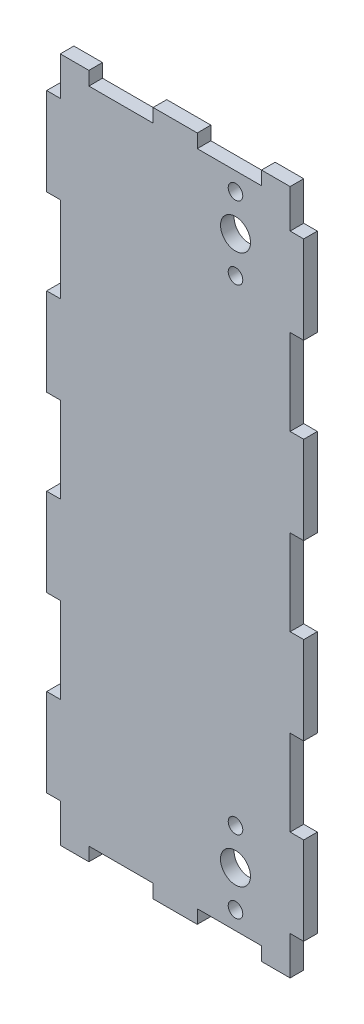
SolidWorks part; units mm, degrees
ref_plane "Front Plane" through (0, 0, 0) normal (0, 0, 1) x (1, 0, 0)
ref_plane "Top Plane" through (0, 0, 0) normal (0, 1, 0) x (1, 0, 0)
ref_plane "Right Plane" through (0, 0, 0) normal (1, 0, 0) x (0, 0, -1)
sketch "Sketch1" plane through (0, 0, 0) normal (0, 0, 1) x (1, 0, 0)
  line L1 (3.175, -25.5685) -> (-56.825, -25.5685)
  line L2 (3.175, -25.5685) -> (3.175, 134.4315)
  line L3 (3.175, 134.4315) -> (-56.825, 134.4315)
  line L4 (-56.825, -25.5685) -> (-56.825, 134.4315)
  dimension "D1" = 160
  dimension "D2" = 60
extrude "Boss-Extrude1" add sketch "Sketch1" against normal up to surface (3.175 mm away)
sketch "Sketch4" plane through (0, 0, 0) normal (0, 0, 1) x (1, 0, 0)
  line L0 (3.175, 134.4315) -> (-56.825, 134.4315) construction
  line L1 (-56.825, 134.4315) -> (-56.825, -25.5685) construction
  line L2 (-56.825, -25.5685) -> (3.175, -25.5685) construction
  line L3 (3.175, -25.5685) -> (0, -25.5685)
  line L4 (0, -25.5685) -> (0, -16.5685)
  line L5 (0, -16.5685) -> (3.175, -16.5685)
  line L6 (3.175, 3.9315) -> (0, 3.9315)
  line L7 (0, 24.1815) -> (0, 3.6815) construction
  line L8 (0, 3.9315) -> (0, 23.9315)
  line L9 (0, 23.9315) -> (3.175, 23.9315)
  line L10 (3.175, 44.4315) -> (0, 44.4315)
  line L11 (0, 64.6815) -> (0, 44.1815) construction
  line L12 (0, 44.4315) -> (0, 64.4315)
  line L13 (0, 64.4315) -> (3.175, 64.4315)
  line L14 (3.175, 84.9315) -> (0, 84.9315)
  line L15 (0, 105.1815) -> (0, 84.6815) construction
  line L16 (0, 84.9315) -> (0, 104.9315)
  line L17 (0, 104.9315) -> (3.175, 104.9315)
  line L18 (3.175, 125.4315) -> (0, 125.4315)
  line L19 (0, 134.4315) -> (0, 125.1815) construction
  line L40 (-31.975, -25.5685) -> (-46.975, -25.5685)
  line L41 (-31.975, -25.5685) -> (-31.975, -22.3935)
  line L42 (0, 125.4315) -> (0, 134.4315)
  line L43 (0, 134.4315) -> (3.175, 134.4315)
  line L45 (3.175, -25.5685) -> (3.175, -16.5685)
  line L46 (3.175, 125.4315) -> (3.175, 134.4315)
  line L47 (3.175, 84.9315) -> (3.175, 104.9315)
  line L48 (3.175, 44.4315) -> (3.175, 64.4315)
  line L49 (3.175, 3.9315) -> (3.175, 23.9315)
  line L58 (-26.825, 134.4315) -> (-26.825, -25.5685) construction
  line L59 (-56.825, 3.9315) -> (-56.825, 23.9315)
  line L60 (-56.825, 44.4315) -> (-56.825, 64.4315)
  line L61 (-56.825, 84.9315) -> (-56.825, 104.9315)
  line L62 (-56.825, 125.4315) -> (-56.825, 134.4315)
  line L63 (-56.825, -25.5685) -> (-56.825, -16.5685)
  line L64 (-53.65, 134.4315) -> (-56.825, 134.4315)
  line L65 (-53.65, 125.4315) -> (-53.65, 134.4315)
  line L66 (-56.825, 125.4315) -> (-53.65, 125.4315)
  line L67 (-53.65, 104.9315) -> (-56.825, 104.9315)
  line L68 (-53.65, 84.9315) -> (-53.65, 104.9315)
  line L69 (-56.825, 84.9315) -> (-53.65, 84.9315)
  line L70 (-53.65, 64.4315) -> (-56.825, 64.4315)
  line L71 (-53.65, 44.4315) -> (-53.65, 64.4315)
  line L72 (-56.825, 44.4315) -> (-53.65, 44.4315)
  line L73 (-53.65, 23.9315) -> (-56.825, 23.9315)
  line L74 (-53.65, 3.9315) -> (-53.65, 23.9315)
  line L75 (-56.825, 3.9315) -> (-53.65, 3.9315)
  line L76 (-53.65, -16.5685) -> (-56.825, -16.5685)
  line L77 (-53.65, -25.5685) -> (-53.65, -16.5685)
  line L78 (-56.825, -25.5685) -> (-53.65, -25.5685)
  line L79 (-31.975, -22.3935) -> (-46.975, -22.3935)
  line L80 (-46.975, -25.5685) -> (-46.975, -22.3935)
  line L81 (-6.675, -25.5685) -> (-6.675, -22.3935)
  line L82 (-21.675, -22.3935) -> (-6.675, -22.3935)
  line L83 (-21.675, -25.5685) -> (-21.675, -22.3935)
  line L84 (-21.675, -25.5685) -> (-6.675, -25.5685)
  line L86 (3.175, 54.4315) -> (-56.825, 54.4315) construction
  line L87 (-21.675, 134.4315) -> (-6.675, 134.4315)
  line L88 (-21.675, 134.4315) -> (-21.675, 131.2565)
  line L89 (-21.675, 131.2565) -> (-6.675, 131.2565)
  line L90 (-6.675, 134.4315) -> (-6.675, 131.2565)
  line L91 (-46.975, 134.4315) -> (-46.975, 131.2565)
  line L92 (-31.975, 131.2565) -> (-46.975, 131.2565)
  line L93 (-31.975, 134.4315) -> (-31.975, 131.2565)
  line L94 (-31.975, 134.4315) -> (-46.975, 134.4315)
  point P10 (3.175, 13.9315)
  point P11 (3.175, 54.4315)
  point P12 (3.175, 94.9315)
  point P69 (-56.825, 94.9315)
  point P70 (-56.825, 54.4315)
  point P71 (-56.825, 13.9315)
  dimension "D1" = 10
  dimension "D2" = 10
  dimension "D3" = 10
  dimension "D4" = 9
  dimension "D5" = 9
  dimension "D6" = 0
  dimension "D7" = 3.175
  dimension "D8" = 15
  dimension "D9" = 3.175
  dimension "D10" = 9.85
  dimension "D11" = 3.175
extrude "Cut-Extrude2" cut sketch "Sketch4" against normal up to surface (3.175 mm away) up to face at (-26.825, 54.4315, -3.175)
sketch "Sketch5" plane through (0, 0, 0) normal (0, 0, 1) x (1, 0, 0)
  line L1 (-6.675, -22.3935) -> (-21.675, -22.3935) construction
  line L2 (0, 23.9315) -> (0, 3.9315) construction
  line L3 (0, -16.5685) -> (0, -25.5685) construction
  line L4 (-9.25, -9.6435) -> (-16.25, -9.6435) construction
  line L5 (0, 54.4315) -> (-53.65, 54.4315) construction
  line L6 (0, 64.4315) -> (0, 44.4315) construction
  line L7 (-53.65, 44.4315) -> (-53.65, 64.4315) construction
  circle A0 centre (-12.75, -9.6435) radius 3.5
  circle A1 centre (-12.75, -18.1435) radius 1.7
  circle A2 centre (-12.75, -1.1435) radius 1.7
  circle A3 centre (-12.75, 127.0065) radius 1.7
  circle A4 centre (-12.75, 118.5065) radius 3.5
  circle A5 centre (-12.75, 110.0065) radius 1.7
  dimension "D1" = 7
  dimension "D5" = 3.4
  dimension "D2" = 12.75
  dimension "D3" = 12.75
  dimension "D4" = 8.5
  dimension "D6" = 12.75
extrude "Cut-Extrude3" cut sketch "Sketch5" against normal up to surface (3.175 mm away) up to face at (-26.825, 54.4315, -3.175)
